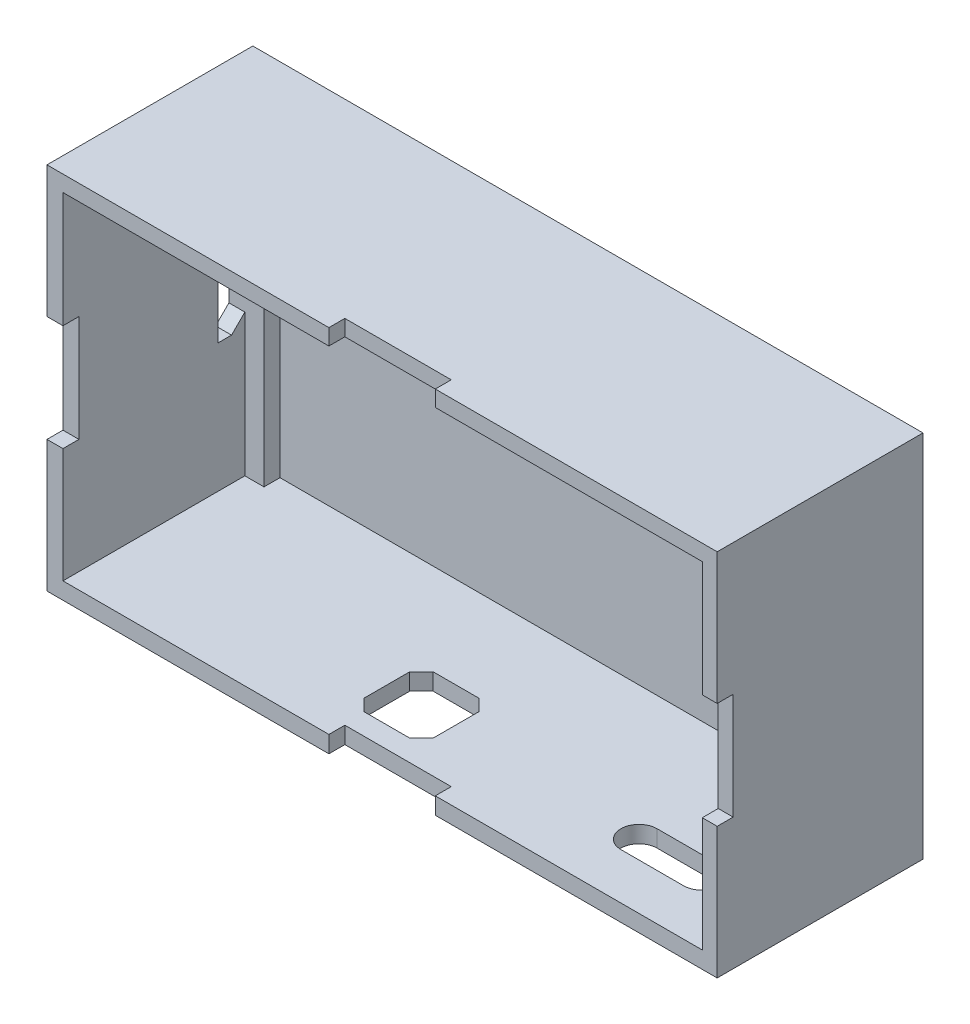
SolidWorks part; units mm, degrees
ref_plane "Alzado" through (0, 0, 0) normal (0, 0, 1) x (1, 0, 0)
ref_plane "Planta" through (0, 0, 0) normal (0, 1, 0) x (1, 0, 0)
ref_plane "Vista lateral" through (0, 0, 0) normal (1, 0, 0) x (0, 0, -1)
sketch "Croquis1" plane through (0, 0, 0) normal (0, 0, 1) x (1, 0, 0)
  line L1 (-24.0228, 7.6502) -> (34.1772, 7.6502)
  line L2 (-24.0228, 7.6502) -> (-24.0228, -24.0498)
  line L3 (-24.0228, -24.0498) -> (34.1772, -24.0498)
  line L4 (34.1772, 7.6502) -> (34.1772, -24.0498)
  circle A0 centre (-20.8728, 4.4502) radius 1.55
  circle A1 centre (31.0272, 4.4502) radius 1.55
  circle A2 centre (-20.8728, -20.8498) radius 1.55
  circle A3 centre (31.0272, -20.8498) radius 1.55
  dimension "D3" = 51.9
  dimension "D4" = 3.1
  dimension "D5" = 3.1
  dimension "D6" = 3.15
  dimension "D7" = 25.3
  dimension "D8" = 25.3
  dimension "D9" = 51.9
  dimension "D10" = 3.1
  dimension "D11" = 3.1
  dimension "D12" = 3.2
  dimension "D1" = 58.2
  dimension "D2" = 31.7
extrude "Saliente-Extruir1" add sketch "Croquis1" along normal blind 0.75
sketch "Croquis3" plane through (0, 0, 0) normal (0, 0, -1) x (-1, 0, 0)
  line L1 (-34.1772, 7.6502) -> (24.0228, 7.6502)
  line L2 (-34.1772, 7.6502) -> (-34.1772, -24.0498)
  line L3 (-34.1772, -24.0498) -> (24.0228, -24.0498)
  line L4 (24.0228, 7.6502) -> (24.0228, -24.0498)
  line L5 (27.3228, 9.1502) -> (-35.6772, 9.1502)
  line L6 (27.3228, 9.1502) -> (27.3228, -25.5498)
  line L7 (27.3228, -25.5498) -> (-35.6772, -25.5498)
  line L8 (-35.6772, 9.1502) -> (-35.6772, -25.5498)
  dimension "D1" = 63
  dimension "D2" = 1.5
  dimension "D3" = 1.5
  dimension "D4" = 1.5
extrude "Saliente-Extruir2" add sketch "Croquis3" against normal blind 2.25
sketch "Croquis4" plane through (0, 0, 0) normal (0, 0, 1) x (1, 0, 0)
  line L1 (-27.3228, 9.1502) -> (35.6772, 9.1502)
  line L2 (-27.3228, 9.1502) -> (-27.3228, -25.5498)
  line L3 (-27.3228, -25.5498) -> (35.6772, -25.5498)
  line L4 (35.6772, 9.1502) -> (35.6772, -25.5498)
  line L5 (34.1772, 7.6502) -> (-25.8228, 7.6502)
  line L6 (34.1772, 7.6502) -> (34.1772, -23.9692)
  line L7 (34.1772, -23.9692) -> (-25.8228, -23.9692)
  line L8 (-25.8228, 7.6502) -> (-25.8228, -23.9692)
  dimension "D1" = 1.5
extrude "Saliente-Extruir3" add sketch "Croquis4" along normal blind 9.35
sketch "Croquis5" plane through (0, 0, 0) normal (0, 0, 1) x (1, 0, 0)
  line L0 (34.1772, 7.6502) -> (-24.0228, 7.6502) construction
  line L1 (33.3443, 7.6502) -> (34.2772, 7.6502)
  line L2 (33.3443, 7.6502) -> (33.3443, -23.9692)
  line L3 (33.3443, -23.9692) -> (34.2772, -23.9692)
  line L4 (34.2772, 7.6502) -> (34.2772, -23.9692)
  line L5 (34.1772, -23.9692) -> (34.1772, 7.6502) construction
  dimension "D1" = 0.1
extrude "Cortar-Extruir1" cut sketch "Croquis5" along normal blind 10
sketch "Croquis6" plane through (0, 0, 0) normal (0, 0, -1) x (-1, 0, 0)
  line L1 (-34.2772, 7.6502) -> (-33.3443, 7.6502)
  line L2 (-34.2772, 7.6502) -> (-34.2772, -23.9692)
  line L3 (-34.2772, -23.9692) -> (-33.3443, -23.9692)
  line L4 (-33.3443, 7.6502) -> (-33.3443, -23.9692)
extrude "Saliente-Extruir4" add sketch "Croquis6" against normal up to surface (0.75 mm away) up to face at (-19.3228, -20.8498, 0.75)
sketch "Croquis7" plane through (0, -23.9692, 0) normal (0, 1, 0) x (1, 0, 0)
  line L0 (34.2772, -9.35) -> (34.2772, -0.75) construction
  line L1 (30.2772, -5.25) -> (23.9772, -5.25)
  line L2 (30.2772, -5.25) -> (30.2772, -8.35)
  line L3 (30.2772, -8.35) -> (23.9772, -8.35)
  line L4 (23.9772, -5.25) -> (23.9772, -8.35)
  line L5 (34.2772, -0.75) -> (-24.0228, -0.75) construction
  dimension "D1" = 4
  dimension "D2" = 6.3
  dimension "D3" = 3.1
  dimension "D4" = 4.5
extrude "Cortar-Extruir2" cut sketch "Croquis7" against normal blind 10
sketch "Croquis9" plane through (0, 0, 9.35) normal (0, 0, 1) x (1, 0, 0)
  line L1 (-27.3228, 9.1502) -> (35.6772, 9.1502)
  line L2 (-27.3228, 9.1502) -> (-27.3228, -25.5498)
  line L3 (-27.3228, -25.5498) -> (35.6772, -25.5498)
  line L4 (35.6772, 9.1502) -> (35.6772, -25.5498)
  line L5 (34.2772, -23.9692) -> (-25.8228, -23.9692)
  line L6 (34.2772, -23.9692) -> (34.2772, 7.6502)
  line L7 (34.2772, 7.6502) -> (-25.8228, 7.6502)
  line L8 (-25.8228, -23.9692) -> (-25.8228, 7.6502)
extrude "Saliente-Extruir5" add sketch "Croquis9" along normal blind 10
sketch "Croquis10" plane through (0, -23.9692, 0) normal (0, 1, 0) x (1, 0, 0)
  line L0 (-24.0228, -2.25) -> (-25.8228, -2.25) construction
  line L1 (-2.1228, -9.35) -> (4.3772, -9.35)
  line L2 (-2.1228, -9.35) -> (-2.1228, -15.85)
  line L3 (-2.1228, -15.85) -> (4.3772, -15.85)
  line L4 (4.3772, -9.35) -> (4.3772, -15.85)
  line L5 (-25.8228, -19.35) -> (-25.8228, -2.25) construction
  dimension "D1" = 7.1
  dimension "D2" = 23.7
  dimension "D3" = 6.5
  dimension "D4" = 6.5
extrude "Cortar-Extruir3" cut sketch "Croquis10" against normal blind 10
sketch "Croquis11" plane through (0, -23.9692, 0) normal (0, 1, 0) x (1, 0, 0)
  line L0 (-25.8228, -19.35) -> (34.2772, -19.35) construction
  line L1 (22.2772, -11.7) -> (28.1772, -11.7)
  line L3 (22.2772, -14.9) -> (28.1772, -14.9)
  arc A0 (22.2772, -11.7) -> (22.2772, -14.9) centre (22.2772, -13.3) ccw
  arc A1 (28.1772, -14.9) -> (28.1772, -11.7) centre (28.1772, -13.3) ccw
  dimension "D1" = 4.45
extrude "Cortar-Extruir4" cut sketch "Croquis11" against normal blind 10
sketch "Croquis12" plane through (0, -25.5498, 0) normal (0, -1, 0) x (1, 0, 0)
  line L0 (23.9772, 5.25) -> (30.2772, 5.25) construction
  line L1 (23.9772, 8.35) -> (24.3772, 8.35)
  line L2 (23.9772, 8.35) -> (23.9772, 5.25)
  line L3 (23.9772, 5.25) -> (24.3772, 5.25)
  line L4 (24.3772, 8.35) -> (24.3772, 5.25)
  dimension "D1" = 0.4
extrude "Saliente-Extruir6" add sketch "Croquis12" against normal up to surface (1.5806 mm away) up to face at (25.2272, -23.9692, 13.3)
sketch "Croquis13" plane through (-25.8228, 0, 0) normal (1, 0, 0) x (0, 0, -1)
  line L0 (-2.25, -23.9692) -> (-2.25, 7.6502) construction
  line L1 (-6.25, -4.4348) -> (-5, -4.4348)
  line L2 (-6.25, -4.4348) -> (-6.25, -11.8848)
  line L3 (-6.25, -11.8848) -> (-5, -11.8848)
  line L4 (-3.75, -5.6848) -> (-3.75, -10.6348)
  line L5 (-19.35, 7.6502) -> (-2.25, 7.6502) construction
  line L6 (-5, -4.4348) -> (-3.75, -5.6848)
  line L7 (-5, -11.8848) -> (-3.75, -10.6348)
  point P6 (-6.25, -8.1598)
  dimension "D1" = 1.5
  dimension "D3" = 7.45
  dimension "D4" = 15.81
extrude "Cortar-Extruir5" cut sketch "Croquis13" against normal blind 10
sketch "Croquis14" plane through (0, -25.5498, 0) normal (0, -1, 0) x (1, 0, 0)
  line L0 (4.3772, 10.45) -> (3.2772, 9.35)
  line L1 (4.3772, 9.35) -> (4.3772, 15.85) construction
  line L2 (-2.1228, 9.35) -> (4.3772, 9.35) construction
  line L3 (-1.0228, 9.35) -> (-2.1228, 10.45)
  line L4 (-2.1228, 15.85) -> (-2.1228, 9.35) construction
  line L5 (-2.1228, 14.75) -> (-1.0228, 15.85)
  line L6 (4.3772, 15.85) -> (-2.1228, 15.85) construction
  line L7 (3.2772, 15.85) -> (4.3772, 14.75)
  line L8 (-2.1228, 10.45) -> (-2.1228, 9.35)
  line L9 (-2.1228, 9.35) -> (-1.0228, 9.35)
  line L10 (3.2772, 9.35) -> (4.3772, 9.35)
  line L11 (4.3772, 9.35) -> (4.3772, 10.45)
  line L12 (4.3772, 14.75) -> (4.3772, 15.85)
  line L13 (4.3772, 15.85) -> (3.2772, 15.85)
  line L14 (-2.1228, 14.75) -> (-2.1228, 15.85)
  line L15 (-2.1228, 15.85) -> (-1.0228, 15.85)
  dimension "D1" = 1.1
  dimension "D2" = 1.1
  dimension "D3" = 1.1
  dimension "D4" = 1.1
  dimension "D5" = 1.1
  dimension "D6" = 1.1
  dimension "D7" = 1.1
  dimension "D8" = 1.1
extrude "Saliente-Extruir7" add sketch "Croquis14" against normal up to surface (1.5806 mm away) up to face at (27.3272, -23.9692, 6.8)
sketch "Croquis15" plane through (0, 0, 0) normal (0, 0, -1) x (-1, 0, 0)
  line L1 (-35.6772, 9.1502) -> (27.3228, 9.1502)
  line L2 (-35.6772, 9.1502) -> (-35.6772, -25.5498)
  line L3 (-35.6772, -25.5498) -> (27.3228, -25.5498)
  line L4 (27.3228, 9.1502) -> (27.3228, -25.5498)
extrude "Saliente-Extruir8" add sketch "Croquis15" against normal up to surface (0.75 mm away) up to face at (-19.3228, -20.8498, 0.75)
sketch "Croquis16" plane through (0, 0, 19.35) normal (0, 0, 1) x (1, 0, 0)
  line L1 (-32.2908, -3.1998) -> (-0.8228, -3.1998)
  line L2 (-32.2908, -3.1998) -> (-32.2908, -13.1998)
  line L3 (-32.2908, -13.1998) -> (-0.8228, -13.1998)
  line L4 (49.1039, -3.1998) -> (49.1039, -13.1998)
  line L5 (-0.8228, 14.9477) -> (9.1772, 14.9477)
  line L6 (-0.8228, 14.9477) -> (-0.8228, -3.1998)
  line L7 (-0.8228, -34.6835) -> (9.1772, -34.6835)
  line L8 (9.1772, 14.9477) -> (9.1772, -3.1998)
  line L9 (-27.3228, 9.1502) -> (-27.3228, -25.5498) construction
  line L10 (35.6772, 9.1502) -> (-27.3228, 9.1502) construction
  line L11 (9.1772, -13.1998) -> (9.1772, -34.6835)
  line L12 (-0.8228, -13.1998) -> (-0.8228, -34.6835)
  line L13 (9.1772, -3.1998) -> (49.1039, -3.1998)
  line L14 (9.1772, -13.1998) -> (49.1039, -13.1998)
  point P8 (-32.2908, -8.1998)
  point P10 (4.1772, 14.9477)
  dimension "D1" = 31.5
  dimension "D2" = 17.35
  dimension "D3" = 10
  dimension "D4" = 10
extrude "Cortar-Extruir6" cut sketch "Croquis16" against normal blind 1.5
sketch "Croquis17" plane through (0, -25.5498, 0) normal (0, -1, 0) x (1, 0, 0)
  line L0 (28.1772, 14.9) -> (22.2772, 14.9) construction
  line L1 (22.2772, 15) -> (28.1772, 15)
  line L3 (22.2772, 11.6) -> (28.1772, 11.6)
  line L5 (22.2772, 11.7) -> (28.1772, 11.7) construction
  arc A2 (22.2772, 15) -> (22.2772, 11.6) centre (22.2772, 13.3) ccw
  arc A3 (28.1772, 11.6) -> (28.1772, 15) centre (28.1772, 13.3) ccw
  dimension "D3" = 0.1
  dimension "D4" = 0.1
extrude "Cortar-Extruir8" cut sketch "Croquis17" against normal blind 10
sketch "Croquis22" plane through (-27.3228, 0, 0) normal (-1, 0, 0) x (0, 0, 1)
  line L0 (6.25, -4.4348) -> (6.25, -11.8848)
  line L1 (6.25, -11.8848) -> (5, -11.8848)
  line L2 (5, -11.8848) -> (3.75, -10.6348)
  line L3 (3.75, -10.6348) -> (3.75, -5.6848)
  line L4 (3.75, -5.6848) -> (5, -4.4348)
  line L5 (5, -4.4348) -> (6.25, -4.4348)
extrude "Saliente-Extruir9" add sketch "Croquis22" against normal up to surface (1.5 mm away) up to face at (-25.8228, -8.1797, 14.7)
sketch "Croquis24" plane through (-25.8228, 0, 0) normal (1, 0, 0) x (0, 0, -1)
  line L0 (-2.25, -5.6848) -> (-2.25, -10.6348)
  line L1 (-2.25, -23.9692) -> (-2.25, 7.6502) construction
  line L2 (-2.25, -10.6348) -> (-3.5016, -11.8864)
  line L3 (-3.5016, -11.8864) -> (-4.7516, -11.8864)
  line L4 (-4.7516, -11.8864) -> (-4.7516, -4.4332)
  line L5 (-4.7516, -4.4332) -> (-3.5016, -4.4332)
  line L6 (-3.5016, -4.4332) -> (-2.25, -5.6848)
  line L7 (-19.35, 7.6502) -> (-2.25, 7.6502) construction
  point P4 (-2.25, -8.1598)
  dimension "D1" = 4.95
  dimension "D2" = 1.77
  dimension "D3" = 1.77
  dimension "D4" = 1.25
  dimension "D5" = 1.25
  dimension "D6" = 135
  dimension "D7" = 15.81
extrude "Cortar-Extruir9" cut sketch "Croquis24" against normal blind 10
